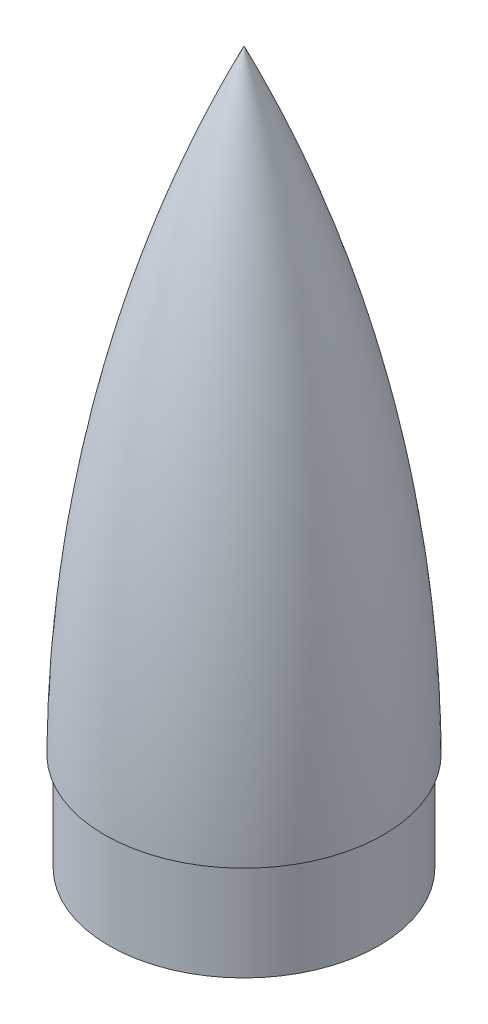
SolidWorks part; units mm, degrees
ref_plane "Front Plane" through (0, 0, 0) normal (0, 0, 1) x (1, 0, 0)
ref_plane "Top Plane" through (0, 0, 0) normal (0, 1, 0) x (1, 0, 0)
ref_plane "Right Plane" through (0, 0, 0) normal (1, 0, 0) x (0, 0, -1)
sketch "Croquis1" plane through (0, 0, 0) normal (1, 0, 0) x (0, 0, -1)
  line L0 (0, 0) -> (0, 290) construction
  line L1 (50, 12) -> (50, 103.2346)
  line L3 (55, 40) -> (55, 0)
  line L4 (55, 0) -> (50, 0)
  line L5 (55, 40) -> (56.8, 40)
  line L6 (0, 290) -> (0, 282.879)
  line L7 (50, 0) -> (0, 0)
  line L8 (0, 0) -> (0, 12)
  line L9 (0, 12) -> (50, 12)
  arc A0 (56.8, 40) -> (0, 290) centre (-538.8692, 36.1164) ccw
  arc A1 (50, 103.2346) -> (0, 282.879) centre (-538.8692, 36.1164) ccw
  arc A2 (53.8001, 39.9804) -> (-2.7139, 288.7214) centre (-538.8692, 36.1164) ccw construction
  dimension "D7" = 595.6818
  dimension "D1" = 110
  dimension "D2" = 1.8
  dimension "D3" = 5
  dimension "D4" = 250
  dimension "D5" = 40
  dimension "D8" = 12
  dimension "D6" = 3
revolve "Revolución1" add sketch "Croquis1" angle 360 about L0
equation "\"R\"= ( \"L\" ^ 2 + \"Rn\" ^ 2 ) / ( 2 * \"Rn\" )"
equation "\"D7@Croquis1\"=\"R\""
equation "\"L\"=250"
equation "\"D4@Croquis1\"=\"L\""
equation "\"Diameter\"=110"
equation "\"D1@Croquis1\"=\"Diameter\""
equation "\"Rn\"= \"Diameter\" / 2"
